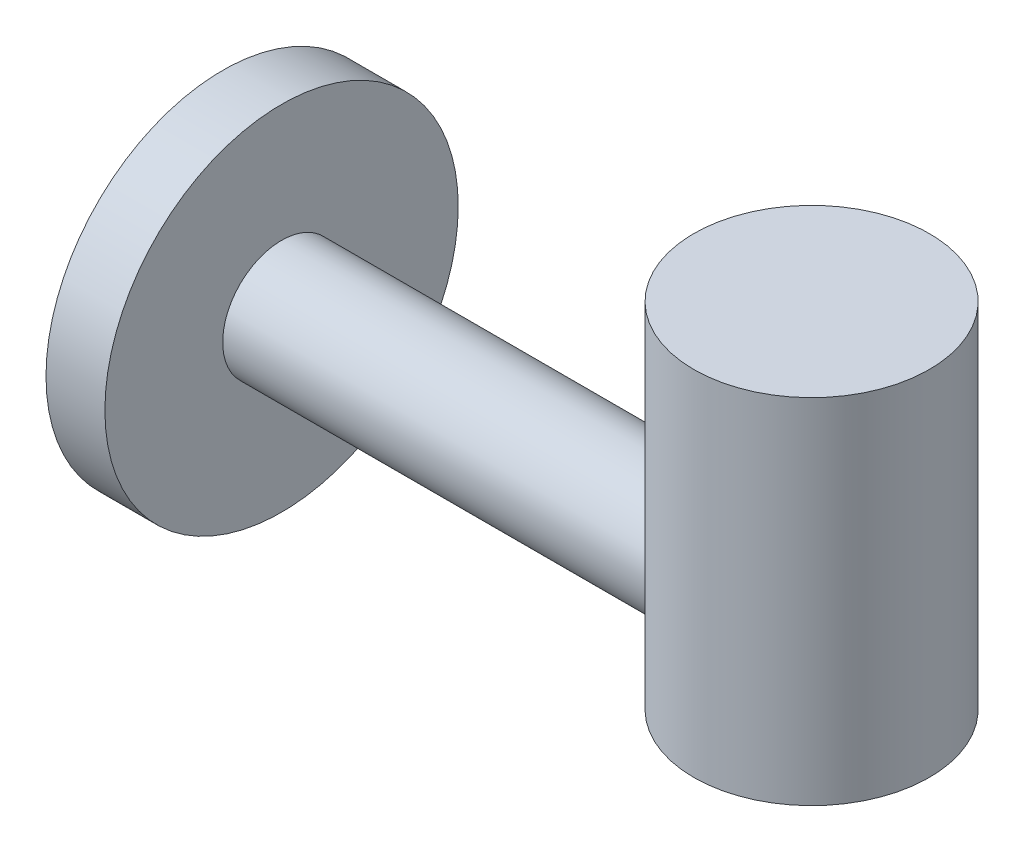
SolidWorks part; units mm, degrees
ref_plane "前视基准面" through (0, 0, 0) normal (0, 0, 1) x (1, 0, 0)
ref_plane "上视基准面" through (0, 0, 0) normal (0, 1, 0) x (1, 0, 0)
ref_plane "右视基准面" through (0, 0, 0) normal (1, 0, 0) x (0, 0, -1)
other "Configuration Table"
sketch "草图1" plane through (0, 0, 0) normal (0, 1, 0) x (1, 0, 0)
  circle A0 centre (0, 0) radius 10
  dimension "D1" = 20
extrude "凸台-拉伸1" add sketch "草图1" along normal blind 30
sketch "草图3" plane through (0, 0, 0) normal (1, 0, 0) x (0, 0, -1)
  line L0 (-10, 0) -> (10, 0) construction
  line L1 (-10, 30) -> (-10, 0) construction
  circle A0 centre (0, 7) radius 5
  dimension "D1" = 10
  dimension "D2" = 7
  dimension "D3" = 10
extrude "凸台-拉伸3" add sketch "草图3" against normal blind 45
sketch "草图4" plane through (-45, 0, 0) normal (-1, 0, 0) x (0, 0, 1)
  circle A0 centre (0, 7) radius 15
  dimension "D1" = 30
extrude "凸台-拉伸4" add sketch "草图4" along normal blind 5
